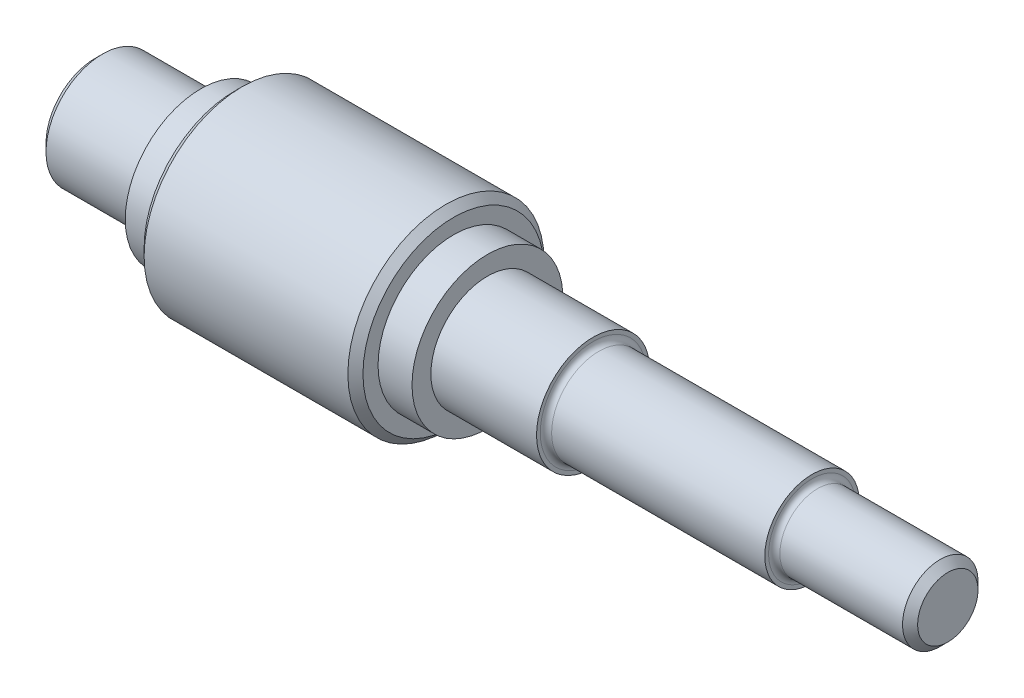
SolidWorks part; units mm, degrees
ref_plane "前视基准面" through (0, 0, 0) normal (0, 0, 1) x (1, 0, 0)
ref_plane "上视基准面" through (0, 0, 0) normal (0, 1, 0) x (1, 0, 0)
ref_plane "右视基准面" through (0, 0, 0) normal (1, 0, 0) x (0, 0, -1)
sketch "草图1" plane through (0, 0, 0) normal (0, 0, 1) x (1, 0, 0)
  line L0 (-113.313, 0) -> (128.0249, 0) construction
  line L1 (-108.9307, 0) -> (-108.9307, 13)
  line L2 (-106.9307, 15) -> (-80.9307, 15)
  line L3 (-80.9307, 15) -> (-80.9307, 20)
  line L4 (-80.9307, 20) -> (-71.9307, 20)
  line L5 (-71.9307, 20) -> (-71.9307, 24)
  line L6 (-69.9307, 26) -> (-15.9307, 26)
  line L7 (-13.9307, 24) -> (-13.9307, 20)
  line L8 (-13.9307, 20) -> (-4.9307, 20)
  line L9 (-4.9307, 20) -> (-4.9307, 15)
  line L10 (-4.9307, 15) -> (23.0693, 15)
  line L11 (23.0693, 15) -> (23.0693, 14)
  line L12 (24.5693, 12.5) -> (81.0693, 12.5)
  line L13 (81.0693, 12.5) -> (81.0693, 11.5)
  line L14 (82.5693, 10) -> (115.0693, 10)
  line L15 (117.0693, 8) -> (117.0693, 0)
  line L16 (-108.9307, 13) -> (-106.9307, 15)
  line L17 (115.0693, 10) -> (117.0693, 8)
  line L18 (-71.9307, 24) -> (-69.9307, 26)
  line L19 (-15.9307, 26) -> (-13.9307, 24)
  line L20 (-108.9307, 0) -> (117.0693, 0)
  arc A0 (24.5693, 12.5) -> (23.0693, 14) centre (24.5693, 14) cw
  arc A1 (82.5693, 10) -> (81.0693, 11.5) centre (82.5693, 11.5) cw
  point P4 (-108.9307, 15)
  point P6 (-13.9307, 26)
  point P9 (-71.9307, 26)
  point P14 (117.0693, 10)
  dimension "D15" = 1.5
  dimension "D1" = 226
  dimension "D2" = 122
  dimension "D3" = 58
  dimension "D4" = 28
  dimension "D5" = 36
  dimension "D6" = 9
  dimension "D7" = 9
  dimension "D8" = 26
  dimension "D9" = 20
  dimension "D10" = 15
  dimension "D11" = 15
  dimension "D12" = 12.5
  dimension "D13" = 10
  dimension "D14" = 20
revolve "旋转1" add sketch "草图1" angle 360 about L20
ref_plane "基准面1" through (0, 0, -10) normal (0, 0, -1) x (-1, 0, 0)
sketch "草图2" plane through (0, 0, -10) normal (0, 0, -1) x (-1, 0, 0)
  line L2 (-110.8087, 3) -> (-88.8087, 3)
  line L5 (-110.8087, -3) -> (-88.8087, -3)
  arc A0 (-110.8087, 3) -> (-110.8087, -3) centre (-110.8087, 0) ccw
  arc A1 (-88.8087, -3) -> (-88.8087, 3) centre (-88.8087, 0) ccw
  dimension "D3" = 6
extrude "切除-拉伸1" cut sketch "草图2" against normal blind 3.5
